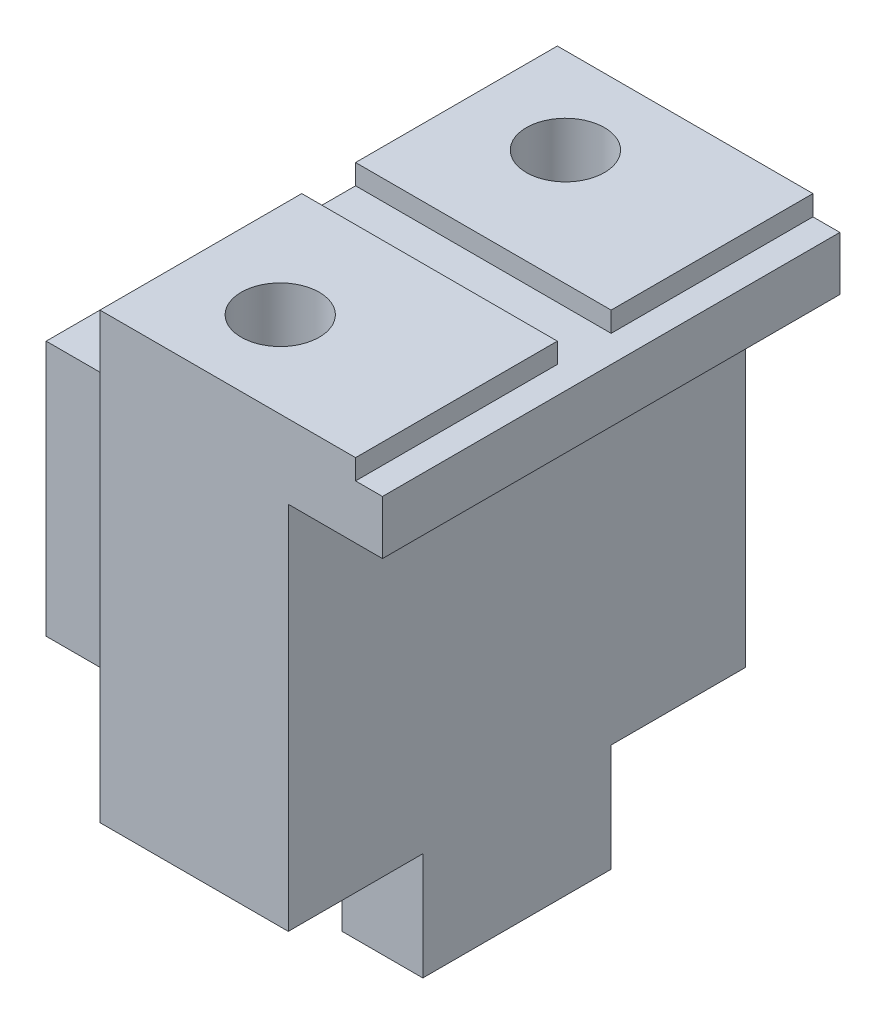
SolidWorks part; units mm, degrees
ref_plane "Alzado" through (0, 0, 0) normal (0, 0, 1) x (1, 0, 0)
ref_plane "Planta" through (0, 0, 0) normal (0, 1, 0) x (1, 0, 0)
ref_plane "Vista lateral" through (0, 0, 0) normal (1, 0, 0) x (0, 0, -1)
sketch "Croquis1" plane through (0, 0, 0) normal (0, 0, 1) x (1, 0, 0)
  line L0 (10.5, 15.75) -> (10.5, 16.25) construction
  line L1 (0, 0) -> (4, 0)
  line L2 (0, 9.5) -> (0, 16.5)
  line L4 (7, 0) -> (7, 13.75)
  line L9 (9.5, 15.75) -> (10.5, 15.75)
  line L12 (10.5, 15.75) -> (10.5, 13.75)
  line L13 (10.5, 16) -> (7, 16) construction
  line L15 (7, 13.75) -> (7, 16.5) construction
  line L16 (0, 9.5) -> (0, 0) construction
  line L17 (3.5, 0) -> (3.5, 16.5) construction
  line L18 (7, 16.5) -> (0, 16.5)
  line L21 (7, 16.5) -> (9.5, 16.5)
  line L22 (9.5, 15.75) -> (9.5, 16.5)
  line L25 (7, 13.75) -> (10.5, 13.75)
  line L27 (0, 0) -> (-7, 0)
  line L29 (0, 9.5) -> (-7, 9.5)
  line L30 (-7, 0) -> (-7, 9.5)
  line L31 (-3.5, 9.5) -> (-3.5, 0) construction
  line L32 (4, 0) -> (7, 0) construction
  line L34 (7, 0) -> (7, -4)
  line L35 (7, -4) -> (4, -4)
  line L36 (4, 0) -> (4, -4)
  line L37 (0, 13) -> (3.5, 13) construction
  line L38 (3.5, 13) -> (7, 13) construction
  dimension "D1" = 16.5
  dimension "D2" = 7
  dimension "D3" = 0.5
  dimension "D4" = 16
  dimension "D5" = 2
  dimension "D6" = 7
  dimension "D7" = 1
  dimension "D8" = 9.5
  dimension "D9" = 7
  dimension "D10" = 7.5
  dimension "D11" = 4
extrude "Saliente-Extruir1" add sketch "Croquis1" along normal blind 7
sketch "Croquis5" plane through (0, 9.5, 0) normal (0, 1, 0) x (1, 0, 0)
  line L0 (-7, 0) -> (0, -7) construction
  circle A0 centre (-3.5, -3.5) radius 1.6
  dimension "D1" = 3.2
extrude "Cortar-Extruir2" cut sketch "Croquis5" against normal blind 13.9
sketch "Croquis6" plane through (0, 9.5, 0) normal (0, 1, 0) x (1, 0, 0)
  circle A0 centre (-3.5, -3.5) radius 2.75
  dimension "D1" = 5.5
extrude "Cortar-Extruir3" cut sketch "Croquis6" against normal blind 3
sketch "Croquis7" plane through (0, 0, 7) normal (0, 0, 1) x (1, 0, 0)
  line L0 (7, -4) -> (7, 13.75) construction
  line L2 (0, 16.5) -> (0, 0)
  line L3 (0, 0) -> (7, 0)
  line L4 (7, 13.75) -> (7, 0)
  line L5 (-7, 0) -> (4, 0) construction
  line L6 (9.5, 16.5) -> (0, 16.5) construction
  line L7 (9.5, 15.75) -> (9.5, 16.5) construction
  line L8 (10.5, 15.75) -> (9.5, 15.75) construction
  line L9 (10.5, 13.75) -> (10.5, 15.75) construction
  line L10 (7, 13.75) -> (10.5, 13.75) construction
  line L11 (9.5, 16.5) -> (0, 16.5)
  line L12 (9.5, 15.75) -> (9.5, 16.5)
  line L13 (10.5, 15.75) -> (9.5, 15.75)
  line L14 (10.5, 13.75) -> (10.5, 15.75)
  line L15 (7, 13.75) -> (10.5, 13.75)
extrude "Saliente-Extruir2" add sketch "Croquis7" along normal blind 5 and the other way blind 12
sketch "Croquis8" plane through (0, 16.5, 0) normal (0, 1, 0) x (1, 0, 0)
  line L0 (0, -3.5) -> (7, -3.5) construction
  line L3 (3.5, -12) -> (3.5, 5) construction
  line L4 (9.5, -12) -> (0, -12) construction
  line L5 (9.5, 5) -> (0, 5) construction
  line L6 (0, -12) -> (0, 5) construction
  line L7 (7, -12) -> (7, 5) construction
  circle A0 centre (3.5, 1.8) radius 1.45
  circle A1 centre (3.5, -8.8) radius 1.45
  point P12 (3.5, -3.5)
  dimension "D1" = 2.9
  dimension "D2" = 3.2
extrude "Cortar-Extruir4" cut sketch "Croquis8" against normal blind 10
sketch "Croquis9" plane through (9.5, 0, 0) normal (1, 0, 0) x (0, 0, -1)
  line L0 (-12, 15.75) -> (5, 15.75) construction
  line L1 (-4.5, 15.75) -> (-2.5, 15.75)
  line L2 (-4.5, 15.75) -> (-4.5, 16.5)
  line L3 (-4.5, 16.5) -> (-2.5, 16.5)
  line L4 (-2.5, 15.75) -> (-2.5, 16.5)
  line L5 (-12, 16.5) -> (5, 16.5) construction
  line L6 (-3.5, 15.75) -> (-3.5, -4) construction
  line L7 (-7, -4) -> (0, -4) construction
  dimension "D1" = 2
extrude "Cortar-Extruir5" cut sketch "Croquis9" against normal blind 10
